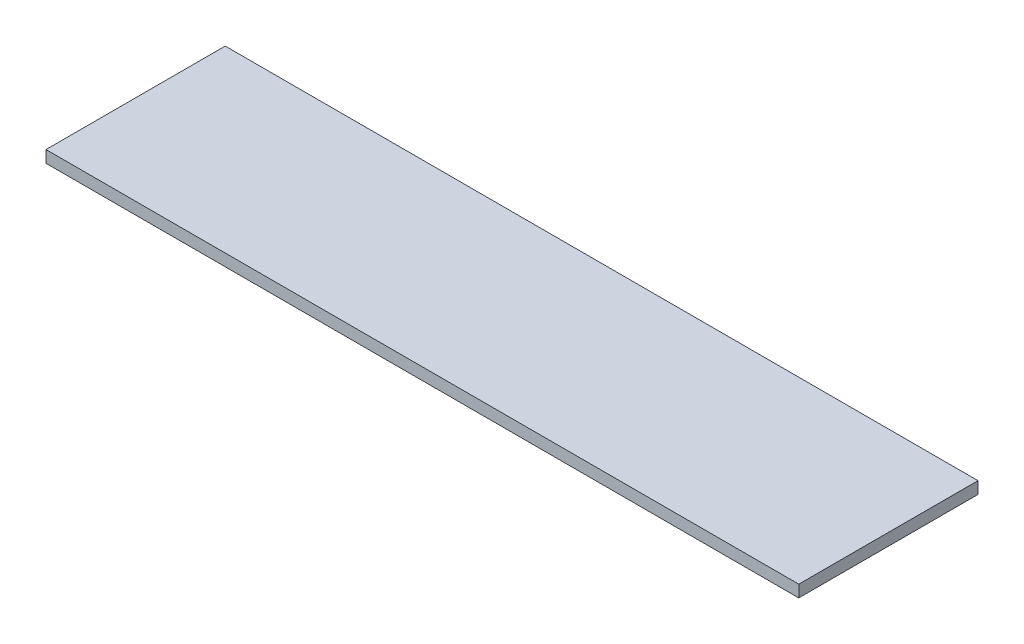
SolidWorks part; units mm, degrees
ref_plane "Front Plane" through (0, 0, 0) normal (0, 0, 1) x (1, 0, 0)
ref_plane "Top Plane" through (0, 0, 0) normal (0, 1, 0) x (1, 0, 0)
ref_plane "Right Plane" through (0, 0, 0) normal (1, 0, 0) x (0, 0, -1)
sketch "Sketch2" plane through (0, 0, 0) normal (0, 1, 0) x (1, 0, 0)
  line L1 (0, 0) -> (800.1, 0)
  line L2 (0, 0) -> (0, 190.5)
  line L3 (0, 190.5) -> (800.1, 190.5)
  line L4 (800.1, 0) -> (800.1, 190.5)
  dimension "D1" = 190.5
  dimension "D2" = 800.1
extrude "Boss-Extrude2" add sketch "Sketch2" along normal blind 12.7
